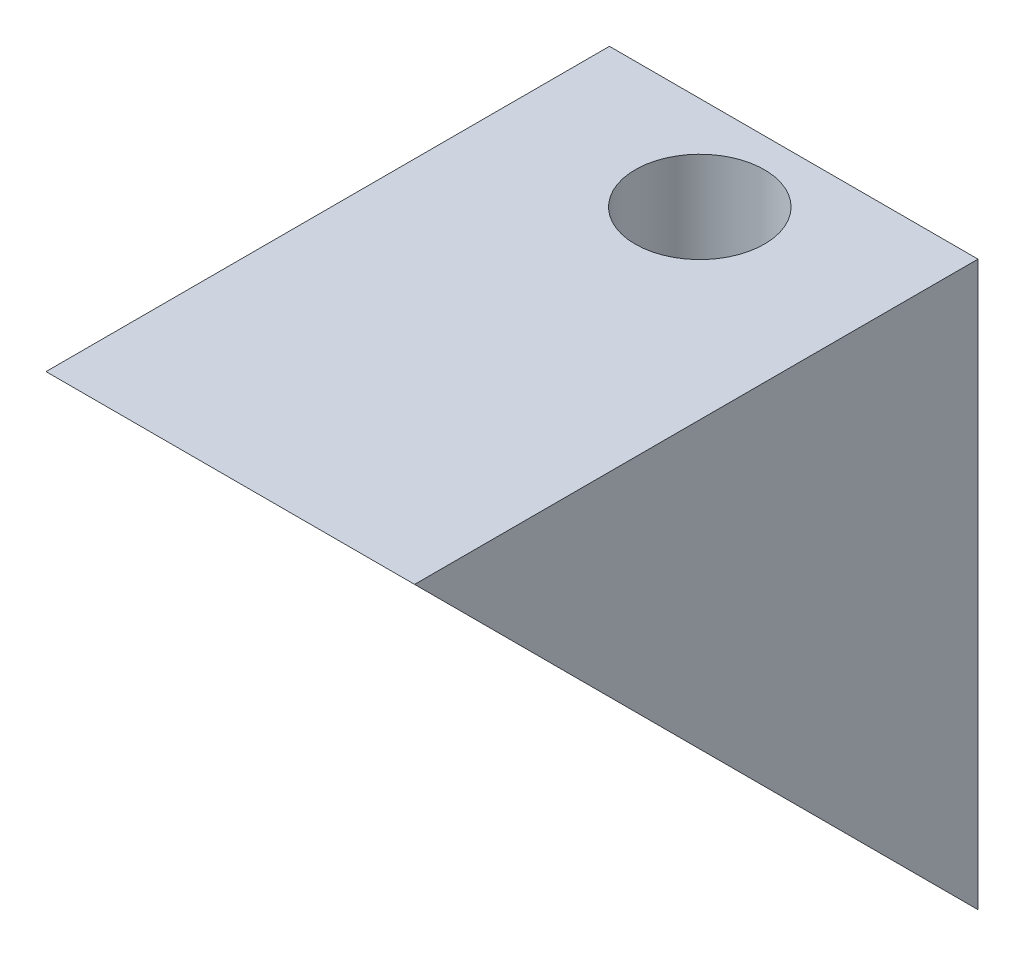
SolidWorks part; units mm, degrees
ref_plane "Front Plane" through (0, 0, 0) normal (0, 0, 1) x (1, 0, 0)
ref_plane "Top Plane" through (0, 0, 0) normal (0, 1, 0) x (1, 0, 0)
ref_plane "Right Plane" through (0, 0, 0) normal (1, 0, 0) x (0, 0, -1)
sketch "Sketch1" plane through (0, 0, 0) normal (1, 0, 0) x (0, 0, -1)
  line L0 (0, 209.1214) -> (0, -209.1214) construction
  line L1 (97.4048, 0) -> (-97.4048, 0) construction
  line L2 (29.1314, 92.5) -> (-29.1314, 92.5) construction
  line L3 (282.5499, -150) -> (-282.5499, -150) construction
  line L4 (24.4822, 10) -> (-24.4822, 10) construction
  line L5 (-12.5, 92.5) -> (-12.5, 10) construction
  line L6 (12.5, 10) -> (12.5, 92.5) construction
  line L7 (97.4048, -90) -> (-97.4048, -90) construction
  point P4 (0, 0)
  point P8 (0, 0)
  point P11 (0, 92.5)
  point P14 (0, -150)
  point P17 (0, 10)
  point P24 (0, -90)
  dimension "D1" = 92.5
  dimension "D2" = 150
  dimension "D3" = 10
  dimension "D4" = 25
  dimension "D5" = 12.5
  dimension "D6" = 100
sketch "Sketch2" plane through (0, 0, 0) normal (1, 0, 0) x (0, 0, -1)
  line L0 (-100, -24.356) -> (20, -144.356)
  line L1 (-100, -24.356) -> (20, -24.356)
  line L2 (20, -24.356) -> (20, -144.356)
  line L3 (0, 209.1214) -> (0, -209.1214) construction
  line L4 (29.1314, 92.5) -> (-29.1314, 92.5) construction
  dimension "D1" = 45
  dimension "D2" = 120
  dimension "D3" = 20
  dimension "D4" = 116.856
extrude "Boss-Extrude1" add sketch "Sketch2" along normal mid plane 78.5
sketch "Sketch4" plane through (0, -24.356, 0) normal (0, 1, 0) x (1, 0, 0)
  line L0 (0, 282.5499) -> (0, -282.5499) construction
  circle A0 centre (0, 0) radius 13.75
  dimension "D1" = 27.5
extrude "Cut-Extrude1" cut sketch "Sketch4" against normal blind 30
sketch "Sketch5" plane through (0, 0, -20) normal (0, 0, -1) x (-1, 0, 0)
  line L0 (0, 0) -> (0, -125.6856) construction
  line L1 (-39.25, -24.356) -> (39.25, -24.356) construction
  circle A0 centre (0, -59.356) radius 3.5
  circle A1 centre (0, -74.356) radius 3.5
  dimension "D1" = 7
  dimension "D2" = 7
  dimension "D3" = 35
  dimension "D4" = 15
sketch "Sketch6" plane through (0, -54.356, 0) normal (0, 1, 0) x (1, 0, 0)
  circle A0 centre (0, 0) radius 10.1
  dimension "D1" = 20.2
ref_plane "Plane1" through (0, -84.356, 0) normal (0, 1, 0) x (1, 0, 0)
sketch "Sketch7" plane through (0, -84.356, 0) normal (0, 1, 0) x (1, 0, 0)
  circle A0 centre (0, 0) radius 9.5
  dimension "D1" = 19
loft "Cut-Loft1" cut profiles "Sketch7", "Sketch6"
extrude "Cut-Extrude2" cut sketch "Sketch5" against normal blind 15
